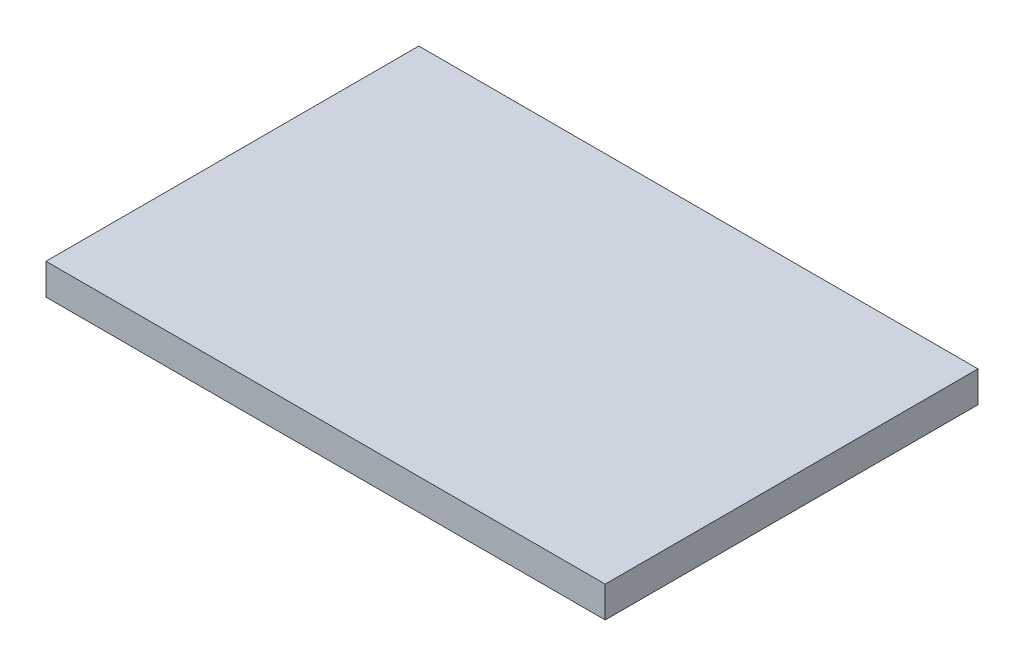
SolidWorks part; units mm, degrees
ref_plane "Front Plane" through (0, 0, 0) normal (0, 0, 1) x (1, 0, 0)
ref_plane "Top Plane" through (0, 0, 0) normal (0, 1, 0) x (1, 0, 0)
ref_plane "Right Plane" through (0, 0, 0) normal (1, 0, 0) x (0, 0, -1)
sketch "Sketch1" plane through (0, 0, 0) normal (0, 1, 0) x (1, 0, 0)
  line L1 (-228.6, -152.4) -> (228.6, -152.4)
  line L2 (-228.6, -152.4) -> (-228.6, 152.4)
  line L3 (-228.6, 152.4) -> (228.6, 152.4)
  line L4 (228.6, -152.4) -> (228.6, 152.4)
  line L5 (-228.6, -152.4) -> (228.6, 152.4) construction
  line L6 (-228.6, 152.4) -> (228.6, -152.4) construction
  point P0 (0, 0)
  dimension "D1" = 304.8
  dimension "D2" = 457.2
extrude "Boss-Extrude1" add sketch "Sketch1" along normal blind 25.4
